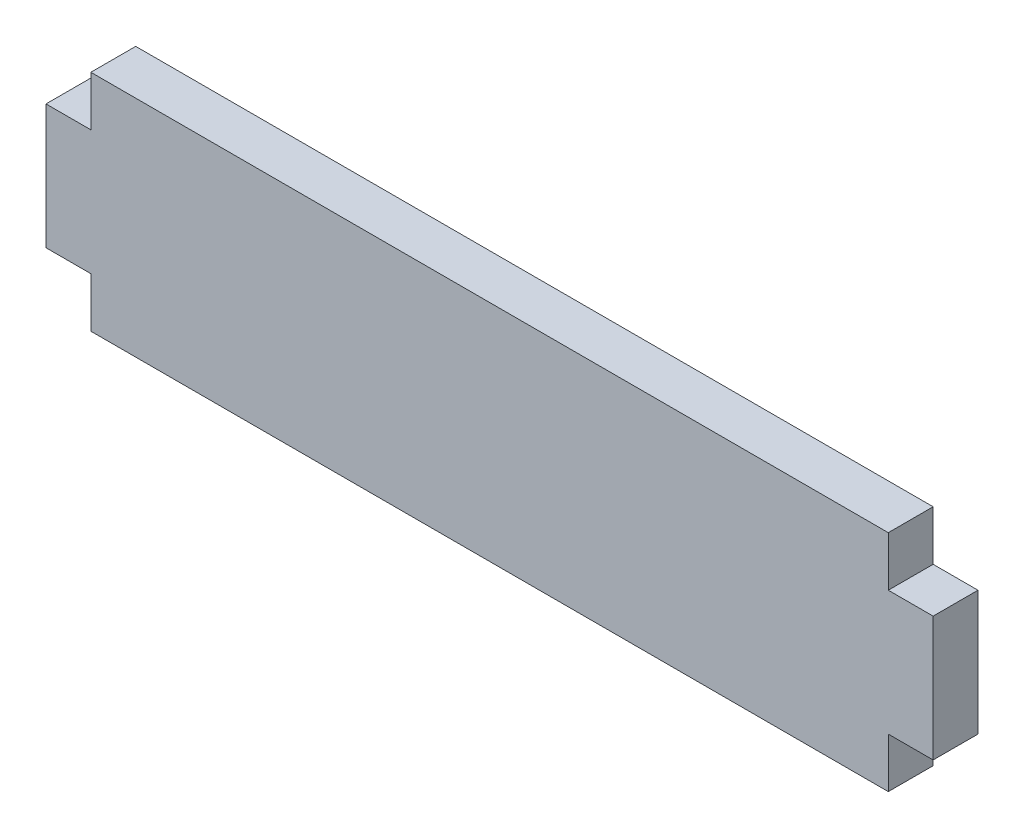
SolidWorks part; units mm, degrees
ref_plane "Front Plane" through (0, 0, 0) normal (0, 0, 1) x (1, 0, 0)
ref_plane "Top Plane" through (0, 0, 0) normal (0, 1, 0) x (1, 0, 0)
ref_plane "Right Plane" through (0, 0, 0) normal (1, 0, 0) x (0, 0, -1)
sketch "Sketch1" plane through (0, 0, 0) normal (0, 0, 1) x (1, 0, 0)
  line L0 (0, 17.8916) -> (142, 17.8916) construction
  line L1 (-160, 62.8916) -> (160, 62.8916)
  line L2 (-160, 62.8916) -> (-160, 42.8916)
  line L3 (-160, -27.1084) -> (160, -27.1084)
  line L4 (160, 62.8916) -> (160, 42.8916)
  line L5 (-160, 62.8916) -> (160, -27.1084) construction
  line L6 (-160, -27.1084) -> (160, 62.8916) construction
  line L7 (160, -7.1084) -> (160, -27.1084)
  line L8 (160, 42.8916) -> (178, 42.8916)
  line L10 (160, -7.1084) -> (178, -7.1084)
  line L11 (178, 42.8916) -> (178, -7.1084)
  line L12 (0, 17.8916) -> (0, -27.1084) construction
  line L13 (-160, -7.1084) -> (-178, -7.1084)
  line L14 (-178, 42.8916) -> (-178, -7.1084)
  line L15 (-160, 42.8916) -> (-178, 42.8916)
  line L16 (-160, -7.1084) -> (-160, -27.1084)
  point P0 (0, 17.8916)
  dimension "D1" = 320
  dimension "D2" = 90
  dimension "D4" = 50
extrude "Boss-Extrude1" add sketch "Sketch1" along normal blind 18
